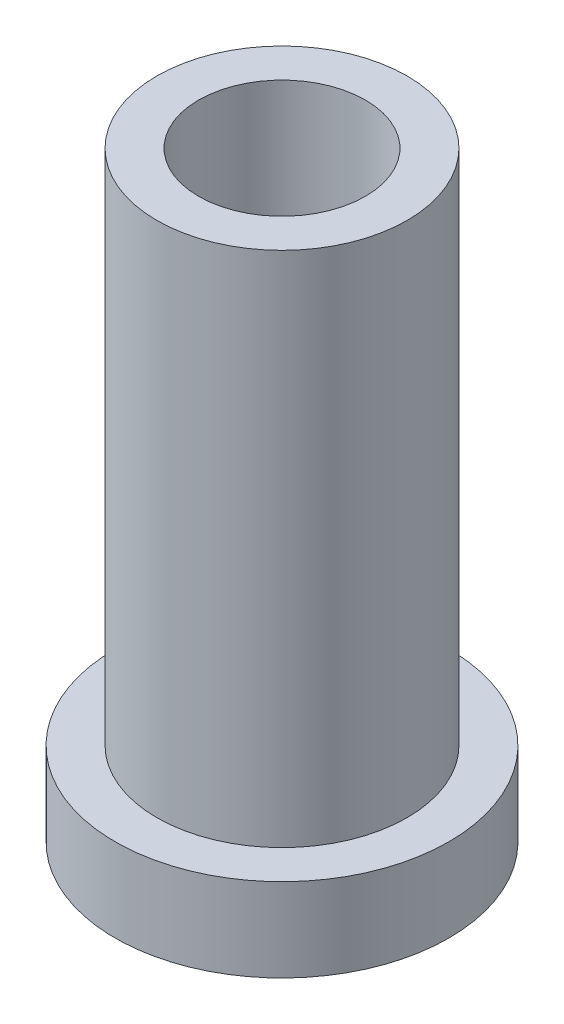
SolidWorks part; units mm, degrees
material "K110"
ref_plane "Front Plane" through (0, 0, 0) normal (0, 0, 1) x (1, 0, 0)
ref_plane "Top Plane" through (0, 0, 0) normal (0, 1, 0) x (1, 0, 0)
ref_plane "Right Plane" through (0, 0, 0) normal (1, 0, 0) x (0, 0, -1)
sketch "Sketch1" plane through (0, 0, 0) normal (0, 0, 1) x (1, 0, 0)
  line L0 (0, 0) -> (10, 0)
  line L1 (10, 0) -> (10, 5)
  line L2 (10, 5) -> (7.5, 5)
  line L3 (7.5, 5) -> (7.5, 36)
  line L4 (7.5, 36) -> (0, 36)
  line L5 (0, 36) -> (0, 0)
  line L6 (0, 41) -> (0, -5) construction
  point P9 (8.75, 5)
  dimension "D1" = 5
  dimension "D2" = 5
  dimension "D3" = 20
  dimension "D4" = 15
  dimension "D5" = 5
  dimension "D6" = 31
revolve "Revolve1" add sketch "Sketch1" angle 360 about L6
sketch "Sketch2" plane through (0, 36, 0) normal (0, 1, 0) x (1, 0, 0)
  circle A0 centre (0, 0) radius 5
  dimension "D1" = 10
extrude "Cut-Extrude1" cut sketch "Sketch2" against normal through all
